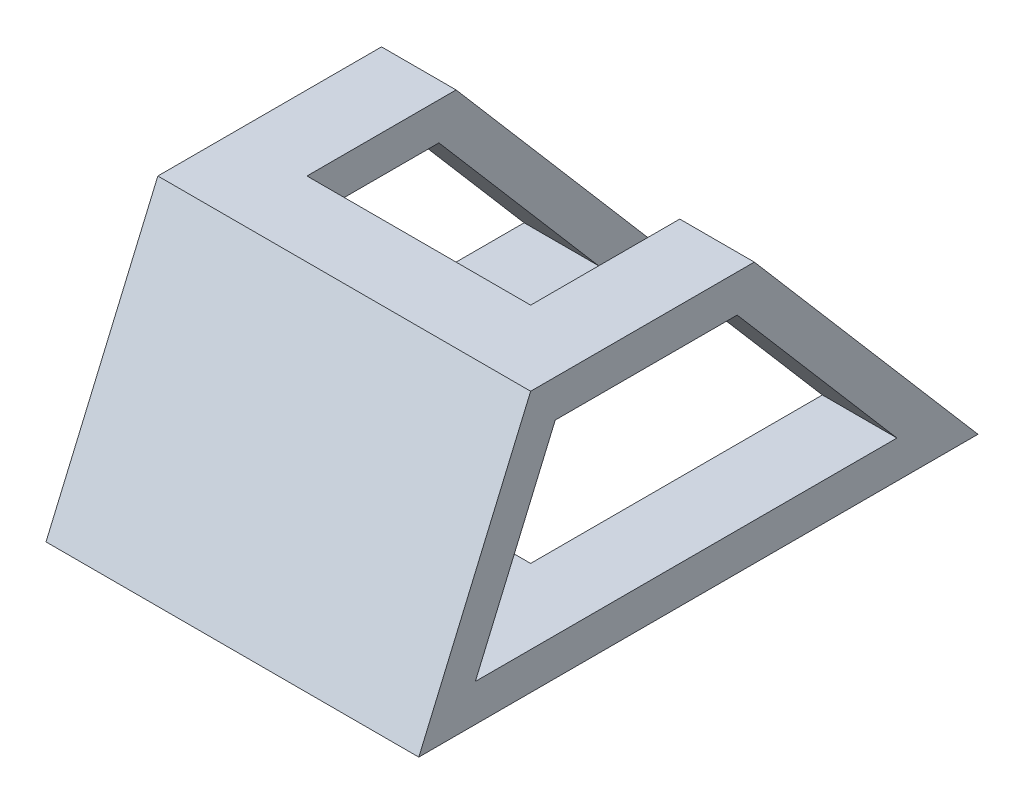
SolidWorks part; units mm, degrees
ref_plane "Ön Düzlem" through (0, 0, 0) normal (0, 0, 1) x (1, 0, 0)
ref_plane "Üst Düzlem" through (0, 0, 0) normal (0, 1, 0) x (1, 0, 0)
ref_plane "Sağ Düzlem" through (0, 0, 0) normal (1, 0, 0) x (0, 0, -1)
sketch "Çizim1" plane through (0, 0, 0) normal (1, 0, 0) x (0, 0, -1)
  line L0 (-50.5778, 44.6444) -> (-80.5778, -25.3556)
  line L1 (-80.5778, -25.3556) -> (69.4222, -25.3556)
  line L2 (69.4222, -25.3556) -> (9.4222, 44.6444)
  line L3 (9.4222, 44.6444) -> (-50.5778, 44.6444)
  line L4 (-43.9838, 34.6444) -> (-65.4124, -15.3556)
  line L5 (-65.4124, -15.3556) -> (47.68, -15.3556)
  line L6 (47.68, -15.3556) -> (4.8229, 34.6444)
  line L7 (4.8229, 34.6444) -> (-43.9838, 34.6444)
  point P2 (0, 0)
  point P5 (0, 0)
  dimension "D1" = 70
  dimension "D2" = 150
  dimension "D3" = 60
  dimension "D4" = 60
  dimension "D5" = 10
extrude "Yükseklik-Ekstrüzyon1" add sketch "Çizim1" along normal blind 100
sketch "Çizim2" plane through (0, 44.6444, 0) normal (0, 1, 0) x (1, 0, 0)
  line L0 (100, 69.4222) -> (0, 69.4222) construction
  line L1 (20, 69.4222) -> (80, 69.4222)
  line L2 (20, 69.4222) -> (20, -30.5778)
  line L3 (20, -30.5778) -> (80, -30.5778)
  line L4 (80, 69.4222) -> (80, -30.5778)
  line L5 (100, 9.4222) -> (0, 9.4222) construction
  line L6 (0, 9.4222) -> (0, -50.5778) construction
  dimension "D1" = 40
  dimension "D2" = 20
  dimension "D3" = 60
extrude "Kes-Ekstrüzyon1" cut sketch "Çizim2" against normal blind 100
